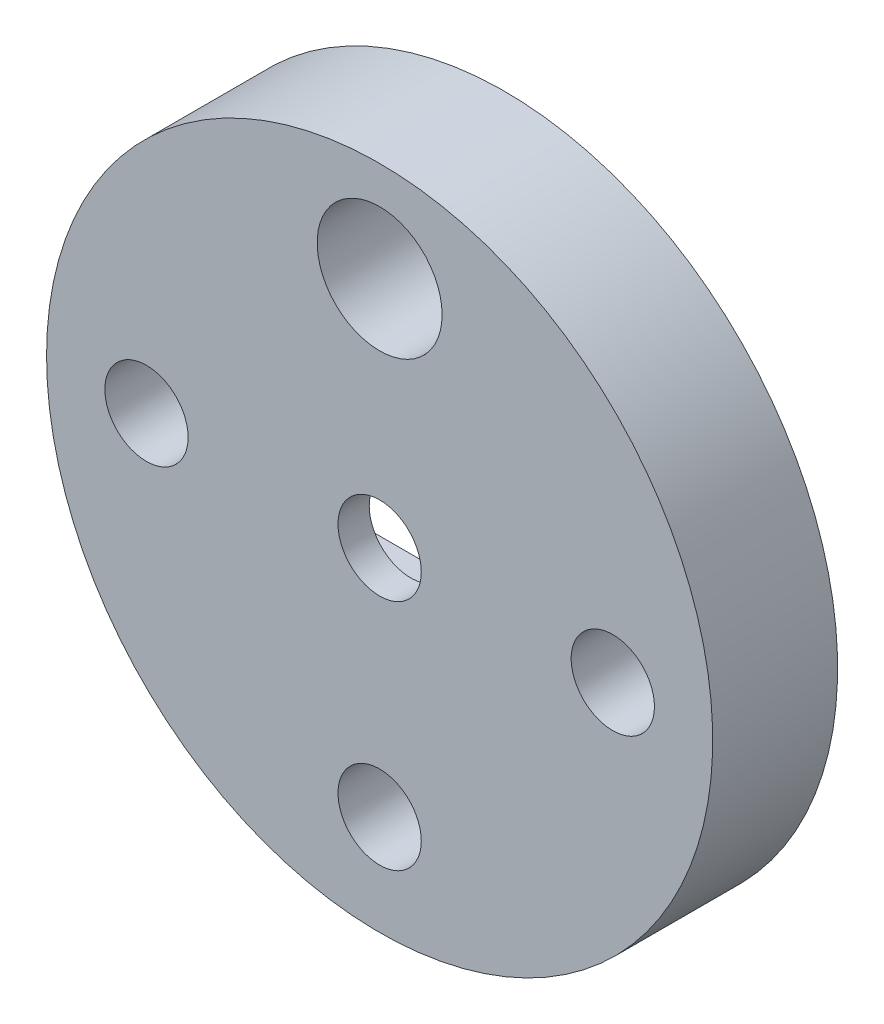
SolidWorks part; units mm, degrees
ref_plane "Front Plane" through (0, 0, 0) normal (0, 0, 1) x (1, 0, 0)
ref_plane "Top Plane" through (0, 0, 0) normal (0, 1, 0) x (1, 0, 0)
ref_plane "Right Plane" through (0, 0, 0) normal (1, 0, 0) x (0, 0, -1)
sketch "Sketch1" plane through (0, 0, 0) normal (0, 0, 1) x (1, 0, 0)
  circle A0 centre (0, 0) radius 25.4
  dimension "D1" = 50.8
extrude "Boss-Extrude1" add sketch "Sketch1" along normal blind 9.525 contours A0
sketch "Sketch2" plane through (0, 0, 0) normal (0, 0, 1) x (1, 0, 0)
  line L1 (-10.3188, 8.7313) -> (10.3187, 8.7313)
  line L2 (-10.3188, 8.7313) -> (-10.3187, -8.7312)
  line L3 (-10.3187, -8.7312) -> (10.3188, -8.7312)
  line L4 (10.3187, 8.7313) -> (10.3188, -8.7312)
  line L5 (-10.3188, 8.7313) -> (10.3188, -8.7312) construction
  line L6 (-10.3187, -8.7312) -> (10.3187, 8.7313) construction
  point P0 (0, 0)
  dimension "D1" = 20.6375
  dimension "D2" = 17.4625
extrude "Cut-Extrude1" cut sketch "Sketch2" along normal blind 7.1437 contours L1 L4 L3 L2
sketch "Sketch3" plane through (0, 0, 7.1437) normal (0, 0, -1) x (-1, 0, 0)
  circle A0 centre (0, 0) radius 3.175
  dimension "D1" = 6.35
extrude "Cut-Extrude9" cut sketch "Sketch3" against normal blind 15.5575 contours A0
sketch "Sketch5" plane through (0, 0, 9.525) normal (0, 0, 1) x (1, 0, 0)
  circle A0 centre (0, 17.78) radius 4.7625
  circle A1 centre (17.78, 0) radius 3.175
  circle A2 centre (0, -17.7689) radius 3.175
  circle A3 centre (-17.78, 0) radius 3.175
  point P8 (0, 0)
  point P10 (0, 0)
  point P11 (0, 0)
  point P12 (0, 0)
  point P13 (0, 0)
  point P14 (0, 0)
  dimension "D1" = 9.525
  dimension "D2" = 6.35
  dimension "D3" = 6.35
  dimension "D4" = 6.35
  dimension "D5" = 17.78
  dimension "D6" = 17.7689
  dimension "D7" = 17.78
  dimension "D8" = 17.78
extrude "Cut-Extrude10" cut sketch "Sketch5" against normal blind 15.5575 contours A2 | A3 | A0 | A1
